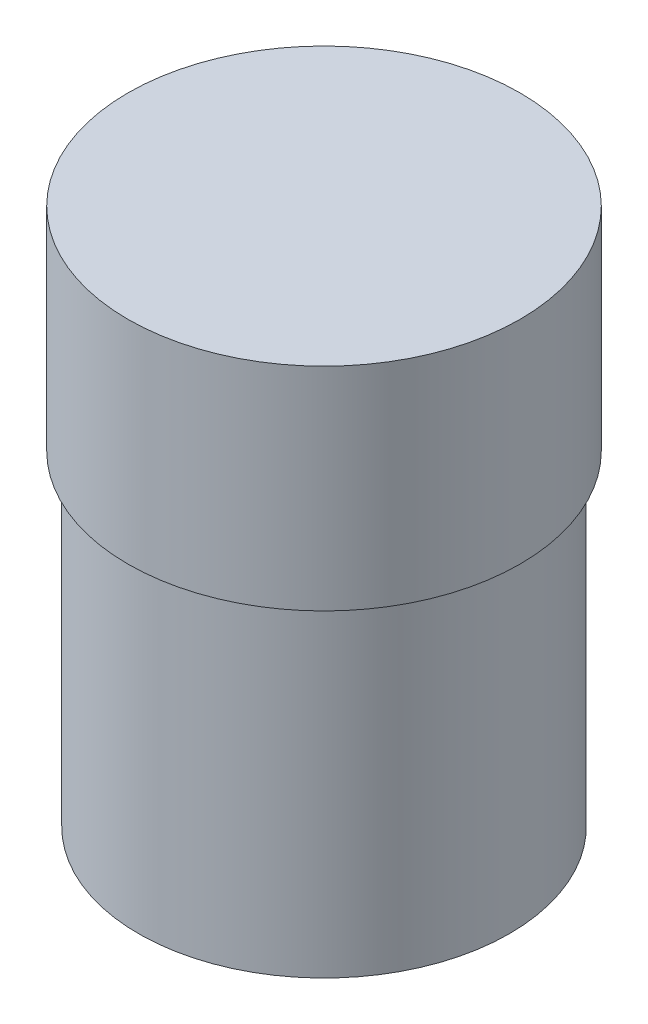
SolidWorks part; units mm, degrees
ref_plane "Front Plane" through (0, 0, 0) normal (0, 0, 1) x (1, 0, 0)
ref_plane "Top Plane" through (0, 0, 0) normal (0, 1, 0) x (1, 0, 0)
ref_plane "Right Plane" through (0, 0, 0) normal (1, 0, 0) x (0, 0, -1)
sketch "Sketch1" plane through (0, 0, 0) normal (0, 0, 1) x (1, 0, 0)
  line L0 (0, 50.7) -> (-18.5, 50.7)
  line L1 (-18.5, 50.7) -> (-18.5, 30.7)
  line L2 (-18.5, 30.7) -> (-17.5, 30.7)
  line L3 (-17.5, 30.7) -> (-17.5, 0)
  line L4 (-17.5, 0) -> (0, 0)
  line L5 (0, 50.7) -> (0, 0)
  line L6 (0, 50.7) -> (0, 63.4853) construction
  dimension "D1" = 20
  dimension "D2" = 30.7
  dimension "D3" = 18.5
  dimension "D4" = 1
revolve "Revolve1" add sketch "Sketch1" angle 360 about L6
